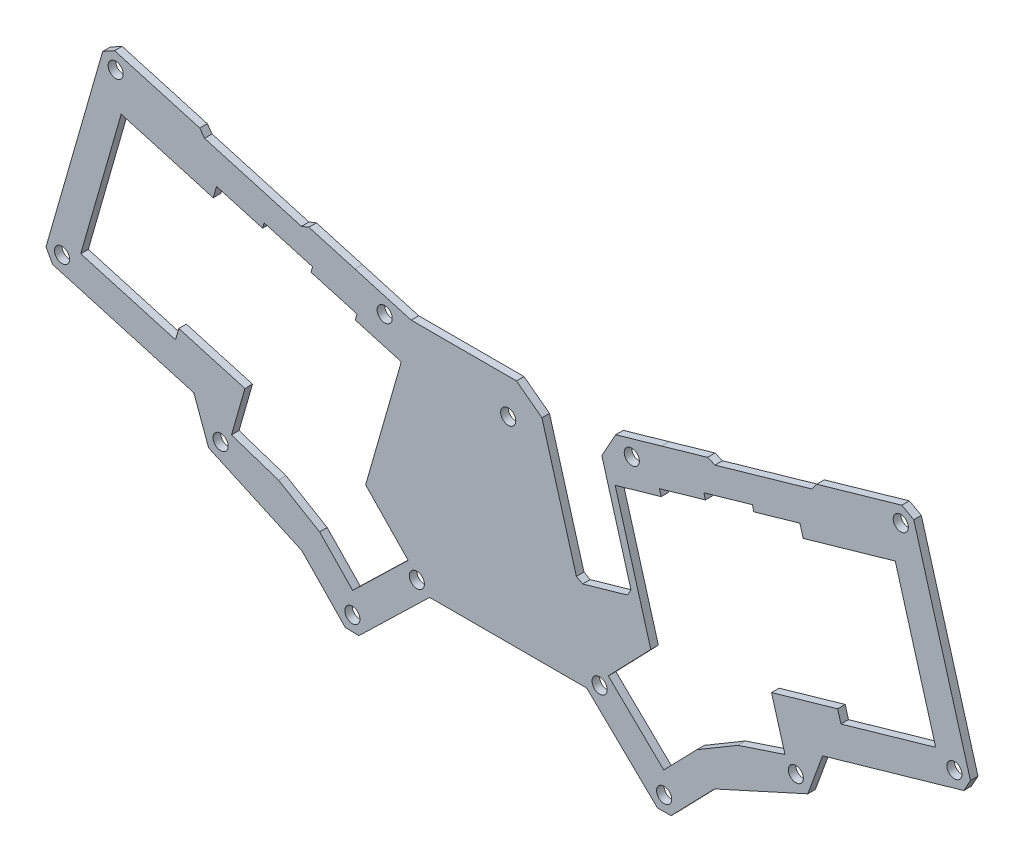
SolidWorks part; units mm, degrees
ref_plane "Plan de face" through (0, 0, 0) normal (0, 0, 1) x (1, 0, 0)
ref_plane "Plan de dessus" through (0, 0, 0) normal (0, 1, 0) x (1, 0, 0)
ref_plane "Plan de droite" through (0, 0, 0) normal (1, 0, 0) x (0, 0, -1)
sketch "Esquisse1" plane through (0, 0, 0) normal (0, 0, 1) x (1, 0, 0)
  line L0 (-121.6461, -32.0475) -> (-108.1875, -28.1884) construction
  line L1 (-108.1875, -28.1884) -> (-104.3283, -41.647) construction
  line L2 (-104.3283, -41.647) -> (-117.7869, -45.5062) construction
  line L3 (-117.7869, -45.5062) -> (-121.6461, -32.0475) construction
  line L4 (-100.1763, -37.9855) -> (-104.0355, -24.5269) construction
  line L5 (-104.0355, -24.5269) -> (-90.5769, -20.6677) construction
  line L6 (-90.5769, -20.6677) -> (-86.7177, -34.1263) construction
  line L7 (-86.7177, -34.1263) -> (-100.1763, -37.9855) construction
  line L8 (-82.5657, -30.4649) -> (-86.4249, -17.0063) construction
  line L9 (-86.4249, -17.0063) -> (-72.9663, -13.1471) construction
  line L10 (-72.9663, -13.1471) -> (-69.1071, -26.6057) construction
  line L11 (-69.1071, -26.6057) -> (-82.5657, -30.4649) construction
  line L12 (-63.6458, -27.5106) -> (-67.505, -14.0519) construction
  line L13 (-67.505, -14.0519) -> (-54.0463, -10.1927) construction
  line L14 (-54.0463, -10.1927) -> (-50.1872, -23.6514) construction
  line L15 (-50.1872, -23.6514) -> (-63.6458, -27.5106) construction
  line L16 (-44.0711, -26.8394) -> (-47.9303, -13.3808) construction
  line L17 (-47.9303, -13.3808) -> (-34.4717, -9.5216) construction
  line L18 (-34.4717, -9.5216) -> (-30.6125, -22.9802) construction
  line L19 (-30.6125, -22.9802) -> (-44.0711, -26.8394) construction
  line L20 (-25.8054, -21.6018) -> (-29.6646, -8.1432) construction
  line L21 (-29.6646, -8.1432) -> (-16.206, -4.284) construction
  line L22 (-16.206, -4.284) -> (-12.3468, -17.7426) construction
  line L23 (-12.3468, -17.7426) -> (-25.8054, -21.6018) construction
  line L24 (-116.4086, -50.3128) -> (-102.95, -46.4536) construction
  line L25 (-102.95, -46.4536) -> (-99.0908, -59.9122) construction
  line L26 (-99.0908, -59.9122) -> (-112.5494, -63.7714) construction
  line L27 (-112.5494, -63.7714) -> (-116.4086, -50.3128) construction
  line L28 (-98.798, -42.7922) -> (-85.3394, -38.933) construction
  line L29 (-85.3394, -38.933) -> (-81.4802, -52.3916) construction
  line L30 (-81.4802, -52.3916) -> (-94.9388, -56.2508) construction
  line L31 (-94.9388, -56.2508) -> (-98.798, -42.7922) construction
  line L32 (-81.1874, -35.2715) -> (-67.7288, -31.4123) construction
  line L33 (-67.7288, -31.4123) -> (-63.8696, -44.8709) construction
  line L34 (-63.8696, -44.8709) -> (-77.3282, -48.7301) construction
  line L35 (-77.3282, -48.7301) -> (-81.1874, -35.2715) construction
  line L36 (-62.2675, -32.3172) -> (-48.8089, -28.458) construction
  line L37 (-48.8089, -28.458) -> (-44.9497, -41.9166) construction
  line L38 (-44.9497, -41.9166) -> (-58.4083, -45.7758) construction
  line L39 (-58.4083, -45.7758) -> (-62.2675, -32.3172) construction
  line L40 (-42.6928, -31.646) -> (-29.2342, -27.7869) construction
  line L41 (-29.2342, -27.7869) -> (-25.375, -41.2455) construction
  line L42 (-25.375, -41.2455) -> (-38.8336, -45.1047) construction
  line L43 (-38.8336, -45.1047) -> (-42.6928, -31.646) construction
  line L44 (-24.4271, -26.4084) -> (-10.9685, -22.5492) construction
  line L45 (-10.9685, -22.5492) -> (-7.1093, -36.0078) construction
  line L46 (-7.1093, -36.0078) -> (-20.5679, -39.867) construction
  line L47 (-20.5679, -39.867) -> (-24.4271, -26.4084) construction
  line L48 (-19.1896, -44.6737) -> (-5.731, -40.8145) construction
  line L49 (-5.731, -40.8145) -> (-1.8718, -54.2731) construction
  line L50 (-1.8718, -54.2731) -> (-15.3304, -58.1323) construction
  line L51 (-15.3304, -58.1323) -> (-19.1896, -44.6737) construction
  line L52 (-37.4554, -49.9113) -> (-23.9967, -46.0521) construction
  line L53 (-23.9967, -46.0521) -> (-20.1376, -59.5107) construction
  line L54 (-20.1376, -59.5107) -> (-33.5962, -63.3699) construction
  line L55 (-33.5962, -63.3699) -> (-37.4554, -49.9113) construction
  line L56 (-57.03, -50.5825) -> (-43.5714, -46.7233) construction
  line L57 (-43.5714, -46.7233) -> (-39.7122, -60.1819) construction
  line L58 (-39.7122, -60.1819) -> (-53.1708, -64.0411) construction
  line L59 (-53.1708, -64.0411) -> (-57.03, -50.5825) construction
  line L60 (-75.9499, -53.5368) -> (-62.4913, -49.6776) construction
  line L61 (-62.4913, -49.6776) -> (-58.6321, -63.1362) construction
  line L62 (-58.6321, -63.1362) -> (-72.0908, -66.9954) construction
  line L63 (-72.0908, -66.9954) -> (-75.9499, -53.5368) construction
  line L64 (-93.5605, -61.0574) -> (-80.1019, -57.1982) construction
  line L65 (-80.1019, -57.1982) -> (-76.2427, -70.6569) construction
  line L66 (-76.2427, -70.6569) -> (-89.7013, -74.516) construction
  line L67 (-89.7013, -74.516) -> (-93.5605, -61.0574) construction
  line L68 (-111.1711, -68.5781) -> (-97.7125, -64.7189) construction
  line L69 (-97.7125, -64.7189) -> (-93.8533, -78.1775) construction
  line L70 (-93.8533, -78.1775) -> (-107.3119, -82.0367) construction
  line L71 (-107.3119, -82.0367) -> (-111.1711, -68.5781) construction
  line L72 (-79.0181, -77.3048) -> (-65.5595, -73.4456) construction
  line L73 (-65.5595, -73.4456) -> (-61.7003, -86.9042) construction
  line L74 (-61.7003, -86.9042) -> (-75.1589, -90.7634) construction
  line L75 (-75.1589, -90.7634) -> (-79.0181, -77.3048) construction
  line L76 (-99.4001, -88.1351) -> (-87.3916, -80.9362)
  line L77 (-87.3916, -80.9362) -> (-80.1927, -92.9448)
  line L78 (-80.1927, -92.9448) -> (-92.2012, -100.1436)
  line L79 (-92.2012, -100.1436) -> (-99.4001, -88.1351)
  line L80 (-120.0498, -100.4367) -> (-110.317, -90.3719)
  line L81 (-110.317, -90.3719) -> (-100.2522, -100.1047)
  line L82 (-100.2522, -100.1047) -> (-109.985, -110.1695)
  line L83 (-109.985, -110.1695) -> (-120.0498, -100.4367)
  line L86 (0.634, -55.7756) -> (-52.9527, -71.1413) construction
  line L89 (-59.2205, -88.2424) -> (-52.9527, -71.1413) construction
  line L96 (-93.4066, -103.0586) -> (-59.4637, -88.3612) construction
  line L97 (-105.418, -115.2057) -> (-93.9754, -103.3509) construction
  line L98 (-126.5332, -96.9919) -> (-107.5003, -115.385) construction
  line L99 (-167.7972, -50.1766) -> (-183.2082, -64.014) construction
  line L100 (-106.3822, -25.4572) -> (-123.6848, -30.4187) construction
  line L101 (-72.1178, -10.6906) -> (-88.4663, -15.3784) construction
  line L102 (-53.2337, -7.6163) -> (-70.5393, -12.5786) construction
  line L103 (-33.6604, -6.9452) -> (-50.9661, -11.9075) construction
  line L104 (-15.3965, -1.7081) -> (-31.745, -6.396) construction
  line L105 (0.5403, -55.2132) -> (-14.6896, -2.0999) construction
  line L106 (-16.199, -60.6113) -> (0.1495, -55.9235) construction
  line L107 (-52.7198, -71.0835) -> (-18.1144, -61.1606) construction
  line L108 (-59.1184, -88.0534) -> (-52.9674, -71.2752) construction
  line L109 (-183.2082, -64.014) -> (-173.1824, -64.9357) construction
  line L113 (-102.2678, -134.438) -> (-84.7238, -116.3191) construction
  line L114 (-84.7238, -116.3191) -> (-47.2969, -99.2981) construction
  line L115 (-47.2969, -99.2981) -> (-41.4917, -83.4594) construction
  line L116 (14.3812, -67.4381) -> (-41.4917, -83.4594) construction
  line L117 (17.8093, -61.2536) -> (-5.1371, 18.7701) construction
  line L122 (-11.3217, 22.1985) -> (-107.4545, -5.3614) construction
  line L129 (-167.7953, -27.6055) -> (-167.7953, -64.7189) construction
  line L130 (-242.0685, -103.8419) -> (-276.37, -88.2424) construction
  line L131 (-229.5108, -116.8112) -> (-242.0685, -103.8419) construction
  line L138 (-208.9328, -96.8551) -> (-229.5108, -116.8112) construction
  line L139 (-225.5107, -79.6567) -> (-208.9328, -96.8551) construction
  line L140 (-109.3352, -134.5492) -> (-102.2678, -134.438) construction
  line L142 (-5.1371, 18.7701) -> (-11.3217, 22.1985) construction
  line L143 (-211.4691, -30.6868) -> (-225.5107, -79.6567) construction
  line L147 (-114.18, -7.2899) -> (-107.4545, -5.3614) construction
  line L148 (-114.18, -7.2899) -> (-123.7936, -10.0465) construction
  line L154 (-118.7579, -16.9241) -> (-12.0005, 13.6817) construction
  line L155 (-131.531, -101.8802) -> (-105.9239, -126.7133) construction
  line L156 (-105.9239, -126.7133) -> (-89.4162, -109.6646) construction
  line L157 (-128.0696, -96.8789) -> (-106.0575, -118.2258)
  line L158 (-106.0575, -118.2258) -> (-92.9354, -104.6737)
  line L161 (1.8709, -56.4612) -> (-35.7408, -67.2462)
  line L162 (1.8709, -56.4612) -> (-14.1861, -0.4639)
  line L163 (-14.1861, -0.4639) -> (-50.7166, -10.9388)
  line L164 (-50.7166, -10.9388) -> (-52.026, -6.3725)
  line L165 (-52.026, -6.3725) -> (-70.2913, -11.61)
  line L166 (-70.2913, -11.61) -> (-70.911, -9.4488)
  line L167 (-70.911, -9.4488) -> (-90.1377, -14.9608)
  line L168 (-90.1377, -14.9608) -> (-89.5177, -17.1231)
  line L169 (-89.5177, -17.1231) -> (-107.783, -22.3606)
  line L170 (-107.783, -22.3606) -> (-107.0938, -24.7639)
  line L171 (-107.0938, -24.7639) -> (-125.3583, -30.0011)
  line L172 (-125.3583, -30.0011) -> (-111.2001, -79.378)
  line L173 (-111.2001, -79.378) -> (-127.3777, -96.1611)
  line L174 (-89.4162, -109.6646) -> (-53.6562, -93.4017) construction
  line L175 (-53.6562, -93.4017) -> (-47.6042, -76.8897) construction
  line L176 (9.2923, -60.5749) -> (-47.6042, -76.8897) construction
  line L177 (9.2923, -60.5749) -> (-12.0005, 13.6817) construction
  line L178 (-229.7336, -25.4495) -> (-211.4691, -30.6868) construction
  line L179 (-229.0444, -23.0462) -> (-229.7336, -25.4495) construction
  line L180 (-173.1824, -64.9357) -> (-167.7972, -60.1004) construction
  line L181 (-247.3097, -17.8087) -> (-229.0444, -23.0462) construction
  line L185 (17.8093, -61.2536) -> (14.3812, -67.4381) construction
  line L186 (-183.2987, -65.7677) -> (-173.2729, -66.6895) construction
  line L187 (-173.2729, -66.6895) -> (-167.8052, -74.7882) construction
  line L190 (-246.6897, -15.6465) -> (-247.3097, -17.8087) construction
  line L191 (-263.9939, -10.6857) -> (-246.6897, -15.6465) construction
  line L192 (-264.6136, -12.8469) -> (-263.9939, -10.6857) construction
  line L193 (-282.8789, -7.6094) -> (-264.6136, -12.8469) construction
  line L194 (-284.1883, -12.1757) -> (-282.8789, -7.6094) construction
  line L195 (-320.7188, -1.7008) -> (-284.1883, -12.1757) construction
  line L196 (-336.2245, -55.7756) -> (-320.7188, -1.7008) construction
  line L197 (-183.2987, -65.7677) -> (-167.8052, -88.0782) construction
  line L198 (-181.8414, -71.5322) -> (-174.8684, -81.0171) construction
  line L199 (-174.8684, -81.0171) -> (-178.3549, -83.9622) construction
  line L200 (-344.8828, -60.5749) -> (-323.5901, 13.6817) construction
  line L201 (-344.8828, -60.5749) -> (-287.9863, -76.8897) construction
  line L202 (-281.9343, -93.4017) -> (-287.9863, -76.8897) construction
  line L203 (-246.1743, -109.6646) -> (-281.9343, -93.4017) construction
  line L204 (-224.3904, -79.378) -> (-208.2128, -96.1611)
  line L205 (-210.2322, -30.0011) -> (-224.3904, -79.378)
  line L206 (-228.4967, -24.7639) -> (-210.2322, -30.0011)
  line L207 (-227.8075, -22.3606) -> (-228.4967, -24.7639)
  line L208 (-246.0728, -17.1231) -> (-227.8075, -22.3606)
  line L209 (-245.4528, -14.9608) -> (-246.0728, -17.1231)
  line L210 (-264.6796, -9.4488) -> (-245.4528, -14.9608)
  line L211 (-265.2993, -11.61) -> (-264.6796, -9.4488)
  line L212 (-283.5645, -6.3725) -> (-265.2993, -11.61)
  line L213 (-284.8739, -10.9388) -> (-283.5645, -6.3725)
  line L217 (0.634, -55.7756) -> (-14.8717, -1.7008) construction
  line L220 (-14.8717, -1.7008) -> (-51.4022, -12.1757) construction
  line L221 (-51.4022, -12.1757) -> (-52.7116, -7.6094) construction
  line L222 (-52.7116, -7.6094) -> (-70.9769, -12.8469) construction
  line L223 (-70.9769, -12.8469) -> (-71.5966, -10.6857) construction
  line L224 (-71.5966, -10.6857) -> (-88.9008, -15.6465) construction
  line L225 (-88.9008, -15.6465) -> (-88.2808, -17.8087) construction
  line L226 (-88.2808, -17.8087) -> (-106.5461, -23.0462) construction
  line L227 (-106.5461, -23.0462) -> (-105.8569, -25.4495) construction
  line L228 (-105.8569, -25.4495) -> (-124.1214, -30.6868) construction
  line L231 (-124.1214, -30.6868) -> (-110.0799, -79.6567) construction
  line L232 (-110.0799, -79.6567) -> (-126.6577, -96.8551) construction
  line L233 (-126.6577, -96.8551) -> (-106.0797, -116.8112) construction
  line L234 (-106.0797, -116.8112) -> (-93.522, -103.8419) construction
  line L235 (-93.522, -103.8419) -> (-59.2205, -88.2424) construction
  line L236 (-321.4044, -0.4639) -> (-284.8739, -10.9388)
  line L237 (-337.4614, -56.4612) -> (-321.4044, -0.4639)
  line L238 (-337.4614, -56.4612) -> (-299.8497, -67.2462)
  line L241 (-229.5331, -118.2258) -> (-242.6551, -104.6737)
  line L242 (-208.2366, -97.573) -> (-229.5331, -118.2258)
  line L243 (-229.6666, -126.7133) -> (-246.1743, -109.6646) construction
  line L244 (-204.0596, -101.8802) -> (-229.6666, -126.7133) construction
  line L245 (-331.2803, 15.8863) -> (-208.2299, -19.3904) construction
  line L246 (-178.3549, -83.9622) -> (-185.8788, -75.0552) construction
  line L247 (-185.8788, -75.0552) -> (-181.8414, -71.5322) construction
  line L248 (-176.7625, -46.6332) -> (-185.5498, -54.5291) construction
  line L249 (-185.5498, -54.5291) -> (-181.1562, -59.4188) construction
  line L250 (-181.1562, -59.4188) -> (-172.3689, -51.5229) construction
  line L251 (-276.4721, -88.0534) -> (-282.6232, -71.2752) construction
  line L252 (-282.8707, -71.0835) -> (-317.4761, -61.1606) construction
  line L253 (-319.3915, -60.6113) -> (-335.74, -55.9235) construction
  line L254 (-336.1309, -55.2132) -> (-320.9009, -2.0999) construction
  line L255 (-320.194, -1.7081) -> (-303.8455, -6.396) construction
  line L256 (-301.9301, -6.9452) -> (-284.6245, -11.9075) construction
  line L257 (-282.3568, -7.6163) -> (-265.0512, -12.5786) construction
  line L258 (-263.4727, -10.6906) -> (-247.1242, -15.3784) construction
  line L259 (-229.2083, -25.4572) -> (-211.9057, -30.4187) construction
  line L260 (-172.3689, -51.5229) -> (-176.7625, -46.6332) construction
  line L261 (-209.0573, -96.9919) -> (-228.0902, -115.385) construction
  line L262 (-230.1725, -115.2057) -> (-241.6151, -103.3509) construction
  line L263 (-242.1839, -103.0586) -> (-276.1268, -88.3612) construction
  line L264 (-276.37, -88.2424) -> (-282.6379, -71.1413) construction
  line L265 (-336.2245, -55.7756) -> (-282.6379, -71.1413) construction
  line L268 (-353.3998, -61.2536) -> (-349.9717, -67.4381) construction
  line L274 (-221.4105, -7.2899) -> (-206.0252, -11.7015) construction
  line L275 (-221.4105, -7.2899) -> (-228.136, -5.3614) construction
  line L276 (-330.4534, 18.7701) -> (-324.2688, 22.1985) construction
  line L277 (-226.2553, -134.5492) -> (-233.3227, -134.438) construction
  line L281 (-324.2688, 22.1985) -> (-228.136, -5.3614) construction
  line L282 (-353.3998, -61.2536) -> (-330.4534, 18.7701) construction
  line L283 (-349.9717, -67.4381) -> (-294.0988, -83.4594) construction
  line L284 (-288.2936, -99.2981) -> (-294.0988, -83.4594) construction
  line L285 (-250.8667, -116.3191) -> (-288.2936, -99.2981) construction
  line L286 (-233.3227, -134.438) -> (-250.8667, -116.3191) construction
  line L288 (-225.6055, -110.1695) -> (-215.5407, -100.4367) construction
  line L289 (-235.3383, -100.1047) -> (-225.6055, -110.1695) construction
  line L290 (-225.2735, -90.3719) -> (-235.3383, -100.1047) construction
  line L291 (-215.5407, -100.4367) -> (-225.2735, -90.3719) construction
  line L292 (-243.3893, -100.1436) -> (-236.1904, -88.1351) construction
  line L293 (-255.3978, -92.9448) -> (-243.3893, -100.1436) construction
  line L294 (-248.1989, -80.9362) -> (-255.3978, -92.9448) construction
  line L295 (-236.1904, -88.1351) -> (-248.1989, -80.9362) construction
  line L296 (-260.4316, -90.7634) -> (-256.5724, -77.3048) construction
  line L297 (-273.8902, -86.9042) -> (-260.4316, -90.7634) construction
  line L298 (-270.031, -73.4456) -> (-273.8902, -86.9042) construction
  line L299 (-256.5724, -77.3048) -> (-270.031, -73.4456) construction
  line L300 (-228.2786, -82.0367) -> (-224.4194, -68.5781) construction
  line L301 (-241.7372, -78.1775) -> (-228.2786, -82.0367) construction
  line L302 (-237.878, -64.7189) -> (-241.7372, -78.1775) construction
  line L303 (-224.4194, -68.5781) -> (-237.878, -64.7189) construction
  line L304 (-245.8892, -74.516) -> (-242.03, -61.0574) construction
  line L305 (-259.3478, -70.6569) -> (-245.8892, -74.516) construction
  line L306 (-255.4886, -57.1982) -> (-259.3478, -70.6569) construction
  line L307 (-242.03, -61.0574) -> (-255.4886, -57.1982) construction
  line L308 (-263.4998, -66.9954) -> (-259.6406, -53.5368) construction
  line L309 (-276.9584, -63.1362) -> (-263.4998, -66.9954) construction
  line L310 (-273.0992, -49.6776) -> (-276.9584, -63.1362) construction
  line L311 (-259.6406, -53.5368) -> (-273.0992, -49.6776) construction
  line L312 (-282.4197, -64.0411) -> (-278.5605, -50.5825) construction
  line L313 (-295.8783, -60.1819) -> (-282.4197, -64.0411) construction
  line L314 (-292.0191, -46.7233) -> (-295.8783, -60.1819) construction
  line L315 (-278.5605, -50.5825) -> (-292.0191, -46.7233) construction
  line L316 (-301.9944, -63.3699) -> (-298.1352, -49.9113) construction
  line L317 (-315.453, -59.5107) -> (-301.9944, -63.3699) construction
  line L318 (-311.5938, -46.0521) -> (-315.453, -59.5107) construction
  line L319 (-298.1352, -49.9113) -> (-311.5938, -46.0521) construction
  line L320 (-320.2601, -58.1323) -> (-316.4009, -44.6737) construction
  line L321 (-333.7187, -54.2731) -> (-320.2601, -58.1323) construction
  line L322 (-329.8595, -40.8145) -> (-333.7187, -54.2731) construction
  line L323 (-316.4009, -44.6737) -> (-329.8595, -40.8145) construction
  line L324 (-315.0226, -39.867) -> (-311.1634, -26.4084) construction
  line L325 (-328.4812, -36.0078) -> (-315.0226, -39.867) construction
  line L326 (-324.622, -22.5492) -> (-328.4812, -36.0078) construction
  line L327 (-311.1634, -26.4084) -> (-324.622, -22.5492) construction
  line L328 (-296.7569, -45.1047) -> (-292.8977, -31.646) construction
  line L329 (-310.2155, -41.2455) -> (-296.7569, -45.1047) construction
  line L330 (-306.3563, -27.7869) -> (-310.2155, -41.2455) construction
  line L331 (-292.8977, -31.646) -> (-306.3563, -27.7869) construction
  line L332 (-277.1822, -45.7758) -> (-273.323, -32.3172) construction
  line L333 (-290.6408, -41.9166) -> (-277.1822, -45.7758) construction
  line L334 (-286.7817, -28.458) -> (-290.6408, -41.9166) construction
  line L335 (-273.323, -32.3172) -> (-286.7817, -28.458) construction
  line L336 (-258.2623, -48.7301) -> (-254.4031, -35.2715) construction
  line L337 (-271.7209, -44.8709) -> (-258.2623, -48.7301) construction
  line L338 (-267.8617, -31.4123) -> (-271.7209, -44.8709) construction
  line L339 (-254.4031, -35.2715) -> (-267.8617, -31.4123) construction
  line L340 (-240.6517, -56.2508) -> (-236.7925, -42.7922) construction
  line L341 (-254.1103, -52.3916) -> (-240.6517, -56.2508) construction
  line L342 (-250.2511, -38.933) -> (-254.1103, -52.3916) construction
  line L343 (-236.7925, -42.7922) -> (-250.2511, -38.933) construction
  line L344 (-223.0411, -63.7714) -> (-219.1819, -50.3128) construction
  line L345 (-236.4997, -59.9122) -> (-223.0411, -63.7714) construction
  line L346 (-232.6405, -46.4536) -> (-236.4997, -59.9122) construction
  line L347 (-219.1819, -50.3128) -> (-232.6405, -46.4536) construction
  line L348 (-323.2438, -17.7426) -> (-309.7851, -21.6018) construction
  line L349 (-319.3846, -4.284) -> (-323.2438, -17.7426) construction
  line L350 (-305.926, -8.1432) -> (-319.3846, -4.284) construction
  line L351 (-309.7851, -21.6018) -> (-305.926, -8.1432) construction
  line L352 (-304.978, -22.9802) -> (-291.5194, -26.8394) construction
  line L353 (-301.1188, -9.5216) -> (-304.978, -22.9802) construction
  line L354 (-287.6602, -13.3808) -> (-301.1188, -9.5216) construction
  line L355 (-291.5194, -26.8394) -> (-287.6602, -13.3808) construction
  line L356 (-285.4034, -23.6514) -> (-271.9448, -27.5106) construction
  line L357 (-281.5442, -10.1927) -> (-285.4034, -23.6514) construction
  line L358 (-268.0856, -14.0519) -> (-281.5442, -10.1927) construction
  line L359 (-271.9448, -27.5106) -> (-268.0856, -14.0519) construction
  line L360 (-266.4834, -26.6057) -> (-253.0248, -30.4649) construction
  line L361 (-262.6242, -13.1471) -> (-266.4834, -26.6057) construction
  line L362 (-249.1656, -17.0063) -> (-262.6242, -13.1471) construction
  line L363 (-253.0248, -30.4649) -> (-249.1656, -17.0063) construction
  line L364 (-248.8728, -34.1263) -> (-235.4142, -37.9855) construction
  line L365 (-245.0136, -20.6677) -> (-248.8728, -34.1263) construction
  line L366 (-231.555, -24.5269) -> (-245.0136, -20.6677) construction
  line L367 (-235.4142, -37.9855) -> (-231.555, -24.5269) construction
  line L368 (-217.8036, -45.5062) -> (-213.9444, -32.0475) construction
  line L369 (-231.2622, -41.647) -> (-217.8036, -45.5062) construction
  line L370 (-227.4031, -28.1884) -> (-231.2622, -41.647) construction
  line L371 (-213.9444, -32.0475) -> (-227.4031, -28.1884) construction
  line L372 (-226.2553, -134.5492) -> (-194.0347, -103.3509) construction
  line L373 (-109.3352, -134.5492) -> (-141.5559, -103.3509) construction
  line L374 (-141.5559, -103.3509) -> (-194.0347, -103.3509) construction
  line L375 (-167.7972, -50.1766) -> (-152.3861, -64.014) construction
  line L376 (-162.4119, -64.9357) -> (-167.7972, -60.1004) construction
  line L377 (-162.3376, -66.6895) -> (-167.8052, -74.7882) construction
  line L378 (-152.3118, -65.7677) -> (-167.8052, -88.0782) construction
  line L379 (-163.2254, -51.5229) -> (-158.8318, -46.6332) construction
  line L380 (-154.4381, -59.4188) -> (-163.2254, -51.5229) construction
  line L381 (-150.0445, -54.5291) -> (-154.4381, -59.4188) construction
  line L382 (-158.8318, -46.6332) -> (-150.0445, -54.5291) construction
  line L383 (-149.7316, -75.0552) -> (-153.7691, -71.5322) construction
  line L384 (-157.2555, -83.9622) -> (-149.7316, -75.0552) construction
  line L385 (-160.742, -81.0171) -> (-157.2555, -83.9622) construction
  line L386 (-153.7691, -71.5322) -> (-160.742, -81.0171) construction
  line L387 (-152.3118, -65.7677) -> (-162.3376, -66.6895) construction
  line L388 (-152.3861, -64.014) -> (-162.4119, -64.9357) construction
  line L389 (-206.0252, -11.7015) -> (-129.5654, -11.7015) construction
  line L390 (-119.0708, -62.7964) -> (-130.6498, -22.4155)
  line L391 (-123.5545, -47.16) -> (-127.4136, -33.7014) construction
  line L392 (-120.442, -65.2702) -> (-138.2688, -70.3819)
  line L393 (-140.7426, -69.0107) -> (-154.4194, -21.3141)
  line L394 (-167.1758, -11.7015) -> (-206.0252, -11.7015) construction
  line L395 (-154.4194, -21.3141) -> (-167.1758, -11.7015) construction
  line L396 (-123.7936, -10.0465) -> (-130.6498, -22.4155) construction
  line L397 (-138.2688, -70.3819) -> (-140.7426, -69.0107)
  line L398 (-119.0708, -62.7964) -> (-120.442, -65.2702)
  line L399 (-129.5654, -11.7015) -> (-123.7936, -10.0465) construction
  line L400 (-165.8487, -12.7015) -> (-206.1657, -12.7015) construction
  line L401 (-221.6861, -8.2511) -> (-206.1657, -12.7015) construction
  line L402 (-221.6861, -8.2511) -> (-228.4116, -6.3226) construction
  line L403 (-324.1462, 21.1231) -> (-228.4116, -6.3226) construction
  line L404 (-329.6063, 18.0963) -> (-324.1462, 21.1231) construction
  line L405 (-352.3244, -61.1311) -> (-329.6063, 18.0963) construction
  line L406 (-352.3244, -61.1311) -> (-349.2979, -66.591) construction
  line L407 (-349.2979, -66.591) -> (-293.3347, -82.6382) construction
  line L408 (-287.4987, -98.561) -> (-293.3347, -82.6382) construction
  line L409 (-250.2802, -115.4872) -> (-287.4987, -98.561) construction
  line L410 (-232.8926, -133.4446) -> (-250.2802, -115.4872) construction
  line L411 (-226.6535, -133.5428) -> (-232.8926, -133.4446) construction
  line L412 (-226.6535, -133.5428) -> (-194.4395, -102.3509) construction
  line L413 (-141.1511, -102.3509) -> (-194.4395, -102.3509) construction
  line L414 (-108.937, -133.5428) -> (-141.1511, -102.3509) construction
  line L415 (-108.937, -133.5428) -> (-102.6979, -133.4446) construction
  line L416 (-102.6979, -133.4446) -> (-85.3104, -115.4872) construction
  line L417 (-85.3104, -115.4872) -> (-48.0918, -98.561) construction
  line L418 (-48.0918, -98.561) -> (-42.2558, -82.6382) construction
  line L419 (13.7074, -66.591) -> (-42.2558, -82.6382) construction
  line L420 (16.7339, -61.1311) -> (13.7074, -66.591) construction
  line L421 (16.7339, -61.1311) -> (-5.9842, 18.0963) construction
  line L422 (-5.9842, 18.0963) -> (-11.4443, 21.1231) construction
  line L423 (-11.4443, 21.1231) -> (-107.1789, -6.3226) construction
  line L424 (-113.9044, -8.2511) -> (-107.1789, -6.3226) construction
  line L425 (-113.9044, -8.2511) -> (-124.4792, -11.2834) construction
  line L426 (-167.1758, -12.7015) -> (-206.1657, -12.7015) construction
  line L427 (-113.9044, -8.2511) -> (-123.5179, -11.0078) construction
  line L428 (-165.8487, -12.7015) -> (-154.4194, -21.3141) construction
  line L429 (-130.6498, -22.4155) -> (-124.4792, -11.2834) construction
  line L430 (-208.2366, -97.573) -> (-207.4919, -96.8551)
  line L431 (-207.4919, -96.8551) -> (-208.2128, -96.1611)
  line L432 (-127.3777, -96.1611) -> (-128.0696, -96.8789)
  line L433 (-221.9618, -9.2124) -> (-206.3062, -13.7015)
  line L434 (-164.5217, -13.7015) -> (-206.3062, -13.7015)
  line L435 (-166.1833, -13.7015) -> (-155.2884, -21.9114) construction
  line L436 (-141.5897, -69.6845) -> (-155.2884, -21.9114) construction
  line L437 (-138.3914, -71.4574) -> (-141.5897, -69.6845) construction
  line L438 (-119.7682, -66.1172) -> (-138.3914, -71.4574) construction
  line L439 (-117.9954, -62.9189) -> (-119.7682, -66.1172) construction
  line L440 (-117.9954, -62.9189) -> (-129.5744, -22.538) construction
  line L441 (-129.5744, -22.538) -> (-123.8054, -12.1305) construction
  line L442 (-113.6287, -9.2124) -> (-125.1648, -12.5203)
  line L443 (-113.6287, -9.2124) -> (-106.9033, -7.2839)
  line L444 (-11.5669, 20.0477) -> (-45.3689, 10.3571)
  line L445 (-6.8313, 17.4225) -> (-11.5669, 20.0477)
  line L446 (15.6584, -61.0086) -> (-6.8313, 17.4225)
  line L447 (15.6584, -61.0086) -> (13.0336, -65.7439)
  line L448 (13.0336, -65.7439) -> (-43.0198, -81.817)
  line L449 (-48.8867, -97.824) -> (-43.0198, -81.817)
  line L450 (-85.8969, -114.6554) -> (-48.8867, -97.824)
  line L451 (-103.128, -132.4513) -> (-85.8969, -114.6554)
  line L452 (-108.5388, -132.5364) -> (-103.128, -132.4513)
  line L453 (-108.5388, -132.5364) -> (-136.6152, -105.3509)
  line L454 (-140.7463, -101.3509) -> (-194.8443, -101.3509) construction
  line L455 (-227.0517, -132.5364) -> (-198.9754, -105.3509)
  line L456 (-227.0517, -132.5364) -> (-232.4625, -132.4513)
  line L457 (-232.4625, -132.4513) -> (-249.6936, -114.6554)
  line L458 (-249.6936, -114.6554) -> (-286.7038, -97.824)
  line L459 (-286.7038, -97.824) -> (-292.5707, -81.817)
  line L460 (-348.6241, -65.7439) -> (-292.5707, -81.817)
  line L461 (-351.2489, -61.0086) -> (-348.6241, -65.7439)
  line L462 (-351.2489, -61.0086) -> (-328.7592, 17.4225)
  line L463 (-328.7592, 17.4225) -> (-324.0237, 20.0477)
  line L464 (-324.0237, 20.0477) -> (-228.6872, -7.2839)
  line L465 (-221.9618, -9.2124) -> (-228.6872, -7.2839)
  line L466 (-166.1833, -13.7015) -> (-206.3062, -13.7015) construction
  line L467 (-113.6287, -9.2124) -> (-123.8054, -12.1305) construction
  line L468 (-130.6498, -22.4155) -> (-125.1648, -12.5203)
  line L469 (-154.4194, -21.3141) -> (-164.5217, -13.7015)
  line L470 (-132.4841, -109.3509) -> (-203.1064, -109.3509) construction
  line L471 (-140.7463, -109.3509) -> (-194.8443, -109.3509) construction
  line L472 (-92.9354, -104.6737) -> (-76.6212, -95.0127)
  line L473 (-227.0517, -132.5364) -> (-194.8443, -101.3509) construction
  line L474 (-108.5388, -132.5364) -> (-140.7463, -101.3509) construction
  line L475 (-76.6212, -95.0127) -> (-57.9612, -88.8254)
  line L476 (-57.9612, -88.8254) -> (-63.3014, -70.2021)
  line L477 (-37.0515, -62.6751) -> (-63.3014, -70.2021)
  line L478 (-37.0515, -62.6751) -> (-35.7408, -67.2462)
  line L479 (-242.6551, -104.6737) -> (-258.9693, -95.0127)
  line L480 (-258.9693, -95.0127) -> (-277.6293, -88.8254)
  line L481 (-277.6293, -88.8254) -> (-272.2891, -70.2021)
  line L482 (-298.539, -62.6751) -> (-272.2891, -70.2021)
  line L483 (-298.539, -62.6751) -> (-299.8497, -67.2462)
  line L484 (-66.4927, 2.2629) -> (-65.3792, -1.6212) construction
  line L485 (-85.7183, -3.2488) -> (-47.2672, 7.7746)
  line L486 (-88.6965, -2.0643) -> (-85.7183, -3.2488)
  line L487 (-45.3689, 10.3571) -> (-47.2672, 7.7746)
  line L488 (-88.6965, -2.0643) -> (-106.9033, -7.2839)
  line L489 (-246.894, -2.0643) -> (-249.8723, -3.2488)
  line L490 (-11.5669, 20.0477) -> (-106.9033, -7.2839) construction
  line L491 (-249.8723, -3.2488) -> (-288.3233, 7.7746)
  line L492 (-290.2216, 10.3571) -> (-288.3233, 7.7746)
  line L493 (-134.5496, -107.3509) -> (-201.0409, -107.3509) construction
  line L494 (-136.6152, -105.3509) -> (-198.9754, -105.3509)
  line L495 (-132.4841, -107.3509) -> (-203.1064, -107.3509) construction
  line L497 (-134.5496, -105.3509) -> (-201.0409, -105.3509) construction
  circle A2 centre (-12.0005, 13.6817) radius 1.6 construction
  circle A3 centre (-12.0005, 13.6817) radius 3
  circle A4 centre (-118.7579, -16.9241) radius 3
  circle A5 centre (9.2923, -60.5749) radius 3
  circle A6 centre (-53.6562, -93.4017) radius 3
  circle A7 centre (-105.9239, -126.7133) radius 3
  circle A8 centre (-131.531, -101.8802) radius 3
  circle A10 centre (-147.4897, -45.973) radius 1.6 construction
  circle A11 centre (-323.5901, 13.6817) radius 3
  circle A12 centre (-188.1008, -45.973) radius 1.6 construction
  circle A14 centre (-204.0596, -101.8802) radius 3
  circle A15 centre (-229.6666, -126.7133) radius 3
  circle A16 centre (-281.9343, -93.4017) radius 3
  circle A17 centre (-344.8828, -60.5749) radius 3
  circle A18 centre (-216.8326, -16.9241) radius 3
  circle A19 centre (-323.5901, 13.6817) radius 1.6 construction
  circle A20 centre (-167.7953, -27.6055) radius 3
  point P138 (-167.7953, -27.6055)
  point P139 (-6.5153, 23.5764)
  point P150 (-169.1046, -23.0392)
  point P200 (19.1875, -66.0599)
  point P203 (-141.5228, -71.3355)
  point P204 (-141.5228, 1.5705)
  point P263 (-133.4062, -12.8029)
  point P264 (-118.5195, -64.7189)
  point P283 (-140.1914, -70.9332)
  point P284 (-157.1758, -11.7015)
  point P405 (-354.778, -66.0599)
  point P406 (-329.0752, 23.5764)
  point P484 (-65.3792, -1.6212)
  dimension "D3" = 3.2
  dimension "D4" = 6
  dimension "D6" = 6
  dimension "D7" = 6
  dimension "D8" = 6
  dimension "D9" = 6
  dimension "D10" = 6
  dimension "D16" = 3.2
  dimension "D14" = 6
  dimension "D2" = 6
  dimension "D5" = 1
  dimension "D11" = 1
  dimension "D18" = 8
  dimension "D20" = 2
  dimension "D21" = 2
extrude "Boss.-Extru.1" add sketch "Esquisse1" along normal blind 3 contours L433 L465 L464 L463 L462 L461 L460 L459 L458 L457 L456 L455 L454 L453 L452 L451 L450 L449 L448 L447 L446 L445 L444 L443 L442 L441 L440 L439 L438 L437 L436 L435 L434 A18 A16 A14 L432 L173 L172 L171 L170 L169 L168 L167 L166 L165 L164
sketch "Esquisse2" plane through (0, 0, 3) normal (0, 0, 1) x (1, 0, 0)
  line L0 (-167.7953, -109.3509) -> (-167.7953, -102.3509) construction
  line L1 (-132.4841, -109.3509) -> (-203.1064, -109.3509) construction
  line L2 (-168.7953, -109.3509) -> (-168.7953, -102.3509)
  line L3 (-166.7953, -109.3509) -> (-166.7953, -102.3509)
  line L4 (-163.7953, -109.3509) -> (-163.7953, -102.3509) construction
  line L5 (-164.7953, -109.3509) -> (-164.7953, -102.3509)
  line L6 (-162.7953, -109.3509) -> (-162.7953, -102.3509)
  line L7 (-159.7953, -109.3509) -> (-159.7953, -102.3509) construction
  line L8 (-160.7953, -109.3509) -> (-160.7953, -102.3509)
  line L9 (-158.7953, -109.3509) -> (-158.7953, -102.3509)
  line L10 (-155.7953, -109.3509) -> (-155.7953, -102.3509) construction
  line L11 (-156.7953, -109.3509) -> (-156.7953, -102.3509)
  line L12 (-154.7953, -109.3509) -> (-154.7953, -102.3509)
  line L13 (-151.7953, -109.3509) -> (-151.7953, -102.3509) construction
  line L14 (-152.7953, -109.3509) -> (-152.7953, -102.3509)
  line L15 (-150.7953, -109.3509) -> (-150.7953, -102.3509)
  line L16 (-147.7953, -109.3509) -> (-147.7953, -102.3509) construction
  line L17 (-148.7953, -109.3509) -> (-148.7953, -102.3509)
  line L18 (-146.7953, -109.3509) -> (-146.7953, -102.3509)
  line L19 (-171.7953, -109.3509) -> (-171.7953, -102.3509) construction
  line L20 (-172.7953, -109.3509) -> (-172.7953, -102.3509)
  line L21 (-170.7953, -109.3509) -> (-170.7953, -102.3509)
  line L22 (-175.7953, -109.3509) -> (-175.7953, -102.3509) construction
  line L23 (-176.7953, -109.3509) -> (-176.7953, -102.3509)
  line L24 (-174.7953, -109.3509) -> (-174.7953, -102.3509)
  line L25 (-179.7953, -109.3509) -> (-179.7953, -102.3509) construction
  line L26 (-180.7953, -109.3509) -> (-180.7953, -102.3509)
  line L27 (-178.7953, -109.3509) -> (-178.7953, -102.3509)
  line L28 (-183.7953, -109.3509) -> (-183.7953, -102.3509) construction
  line L29 (-184.7953, -109.3509) -> (-184.7953, -102.3509)
  line L30 (-182.7953, -109.3509) -> (-182.7953, -102.3509)
  line L31 (-187.7953, -109.3509) -> (-187.7953, -102.3509) construction
  line L32 (-188.7953, -109.3509) -> (-188.7953, -102.3509)
  line L33 (-186.7953, -109.3509) -> (-186.7953, -102.3509)
  arc A0 (-168.7953, -109.3509) -> (-166.7953, -109.3509) centre (-167.7953, -109.3509) ccw
  arc A1 (-166.7953, -102.3509) -> (-168.7953, -102.3509) centre (-167.7953, -102.3509) ccw
  arc A2 (-164.7953, -109.3509) -> (-162.7953, -109.3509) centre (-163.7953, -109.3509) ccw
  arc A3 (-162.7953, -102.3509) -> (-164.7953, -102.3509) centre (-163.7953, -102.3509) ccw
  arc A4 (-160.7953, -109.3509) -> (-158.7953, -109.3509) centre (-159.7953, -109.3509) ccw
  arc A5 (-158.7953, -102.3509) -> (-160.7953, -102.3509) centre (-159.7953, -102.3509) ccw
  arc A6 (-156.7953, -109.3509) -> (-154.7953, -109.3509) centre (-155.7953, -109.3509) ccw
  arc A7 (-154.7953, -102.3509) -> (-156.7953, -102.3509) centre (-155.7953, -102.3509) ccw
  arc A8 (-152.7953, -109.3509) -> (-150.7953, -109.3509) centre (-151.7953, -109.3509) ccw
  arc A9 (-150.7953, -102.3509) -> (-152.7953, -102.3509) centre (-151.7953, -102.3509) ccw
  arc A10 (-148.7953, -109.3509) -> (-146.7953, -109.3509) centre (-147.7953, -109.3509) ccw
  arc A11 (-146.7953, -102.3509) -> (-148.7953, -102.3509) centre (-147.7953, -102.3509) ccw
  arc A12 (-172.7953, -109.3509) -> (-170.7953, -109.3509) centre (-171.7953, -109.3509) ccw
  arc A13 (-170.7953, -102.3509) -> (-172.7953, -102.3509) centre (-171.7953, -102.3509) ccw
  arc A14 (-176.7953, -109.3509) -> (-174.7953, -109.3509) centre (-175.7953, -109.3509) ccw
  arc A15 (-174.7953, -102.3509) -> (-176.7953, -102.3509) centre (-175.7953, -102.3509) ccw
  arc A16 (-180.7953, -109.3509) -> (-178.7953, -109.3509) centre (-179.7953, -109.3509) ccw
  arc A17 (-178.7953, -102.3509) -> (-180.7953, -102.3509) centre (-179.7953, -102.3509) ccw
  arc A18 (-184.7953, -109.3509) -> (-182.7953, -109.3509) centre (-183.7953, -109.3509) ccw
  arc A19 (-182.7953, -102.3509) -> (-184.7953, -102.3509) centre (-183.7953, -102.3509) ccw
  arc A20 (-188.7953, -109.3509) -> (-186.7953, -109.3509) centre (-187.7953, -109.3509) ccw
  arc A21 (-186.7953, -102.3509) -> (-188.7953, -102.3509) centre (-187.7953, -102.3509) ccw
  point P4 (-167.7953, -105.8509)
  point P12 (-163.7953, -105.8509)
  point P19 (-159.7953, -105.8509)
  point P26 (-155.7953, -105.8509)
  point P33 (-151.7953, -105.8509)
  point P40 (-147.7953, -105.8509)
  point P47 (-171.7953, -105.8509)
  point P54 (-175.7953, -105.8509)
  point P61 (-179.7953, -105.8509)
  point P68 (-183.7953, -105.8509)
  point P75 (-187.7953, -105.8509)
  dimension "D1" = 6
  dimension "D2" = 6
